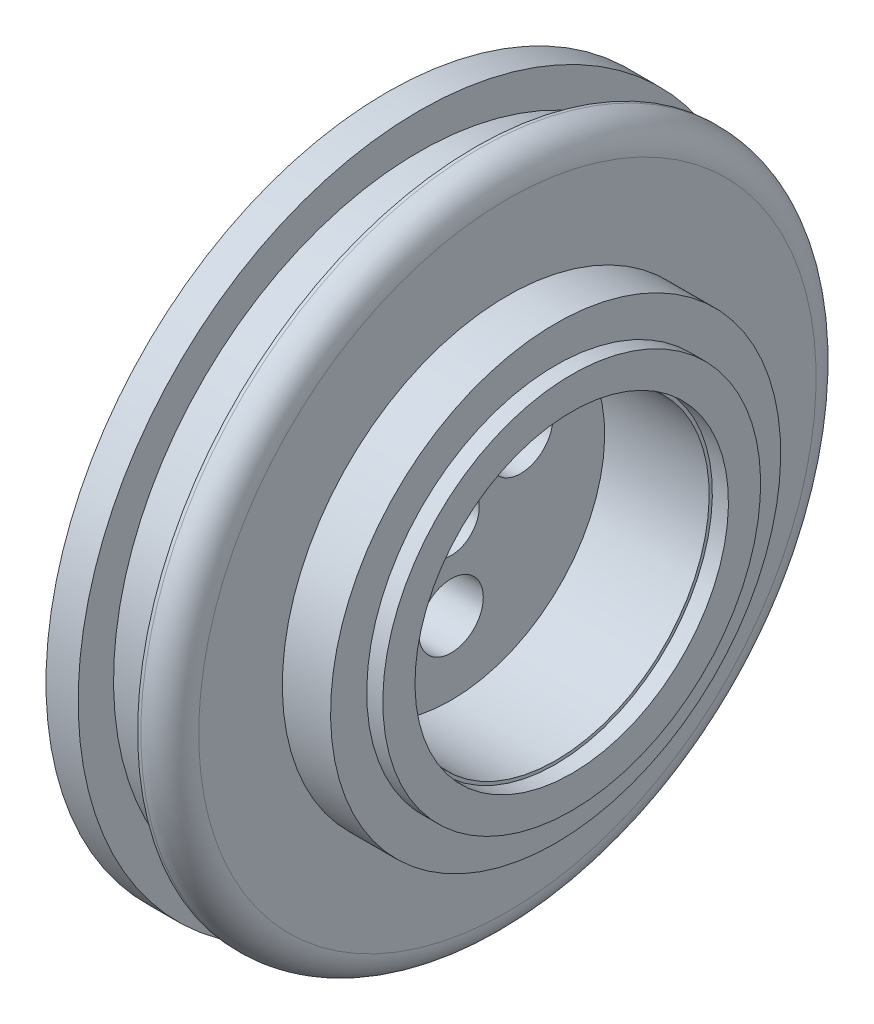
SolidWorks part; units mm, degrees
ref_plane "Front Plane" through (0, 0, 0) normal (0, 0, 1) x (1, 0, 0)
ref_plane "Top Plane" through (0, 0, 0) normal (0, 1, 0) x (1, 0, 0)
ref_plane "Right Plane" through (0, 0, 0) normal (1, 0, 0) x (0, 0, -1)
sketch "Sketch1" plane through (0, 0, 0) normal (0, 0, 1) x (1, 0, 0)
  line L2 (10.5, 14) -> (7.5, 14)
  line L3 (7.5, 14) -> (7.5, 19.2)
  line L4 (5.7, 21) -> (5.5, 21)
  line L5 (5.5, 21) -> (5.5, 19)
  line L6 (5.5, 19) -> (2, 19)
  line L7 (2, 19) -> (2, 21.2)
  line L8 (2, 21.2) -> (0, 21.2)
  line L10 (10.5, 14) -> (10.5, 11.75)
  line L11 (10.5, 11.75) -> (11.5, 11.75)
  line L12 (11.5, 11.75) -> (11.5, 9.75)
  line L13 (11.5, 9.75) -> (10.5, 9.75)
  line L14 (10.5, 9.75) -> (10.5, 9.55)
  line L16 (0, 21.2) -> (0, 0)
  line L17 (0, 0) -> (4, 0)
  line L18 (10.5, 9.55) -> (4, 9.55)
  line L19 (4, 9.55) -> (4, 0)
  arc A0 (7.5, 19.2) -> (5.7, 21) centre (5.7, 19.2) ccw
  point P20 (7.5, 21)
  dimension "D14" = 1.8
  dimension "D1" = 2
  dimension "D2" = 3.5
  dimension "D3" = 19
  dimension "D4" = 2.2
  dimension "D5" = 2
  dimension "D6" = 2
  dimension "D7" = 6.5
  dimension "D8" = 3
  dimension "D9" = 1
  dimension "D10" = 0.2
  dimension "D11" = 14
  dimension "D12" = 9.55
  dimension "D13" = 2
revolve "Revolve1" add sketch "Sketch1" angle 360 about L17
sketch "Sketch2" plane through (0, 0, 0) normal (1, 0, 0) x (0, 0, -1)
  line L0 (0, 0) -> (0, -5) construction
  circle A0 centre (0, 0) radius 1.75
  circle A1 centre (0, -5) radius 2
  circle A2 centre (-4.3301, 2.5) radius 2
  circle A3 centre (4.3301, 2.5) radius 2
  dimension "D1" = 4
  dimension "D3" = 3.5
  dimension "D2" = 5
  dimension "D4" = 3
extrude "Cut-Extrude2" cut sketch "Sketch2" against normal through all and the other way through all
sketch "Sketch3" plane through (7.5, 0, 0) normal (1, 0, 0) x (0, 0, -1)
  line L0 (-1.5776, 13.8) -> (-1.5776, 14.6)
  line L1 (-1.5776, 14.6) -> (-0.75, 17.8)
  line L2 (-0.75, 17.8) -> (0.75, 17.8)
  line L3 (0.75, 17.8) -> (1.5776, 14.6)
  line L4 (1.5776, 14.6) -> (1.5776, 13.8)
  line L5 (1.5776, 13.8) -> (-1.5776, 13.8)
  point P8 (0, 13.8)
  dimension "D1" = 4
  dimension "D2" = 0.8
  dimension "D3" = 14.5
  dimension "D4" = 14.5
  dimension "D5" = 1.5
  dimension "D6" = 13.8
extrude "Boss-Extrude1" [suppressed] add sketch "Sketch3" along normal up to surface (3 mm away)
pattern_circular "CirPattern1" [suppressed] count 17 over 360
sketch "Sketch4" plane through (4, 0, 0) normal (1, 0, 0) x (0, 0, -1)
  circle A0 centre (0, -5) radius 2 construction
  circle A1 centre (0, 0) radius 9.55
  circle A2 centre (0, 0) radius 9.55
  circle A3 centre (4.3301, 2.5) radius 2 construction
  circle A4 centre (0, 0) radius 1.75 construction
  circle A5 centre (-4.3301, 2.5) radius 2 construction
  circle A6 centre (0, -5) radius 2
  circle A7 centre (4.3301, 2.5) radius 2
  circle A8 centre (0, 0) radius 1.75
  circle A9 centre (-4.3301, 2.5) radius 2
  dimension "D1" = 0
